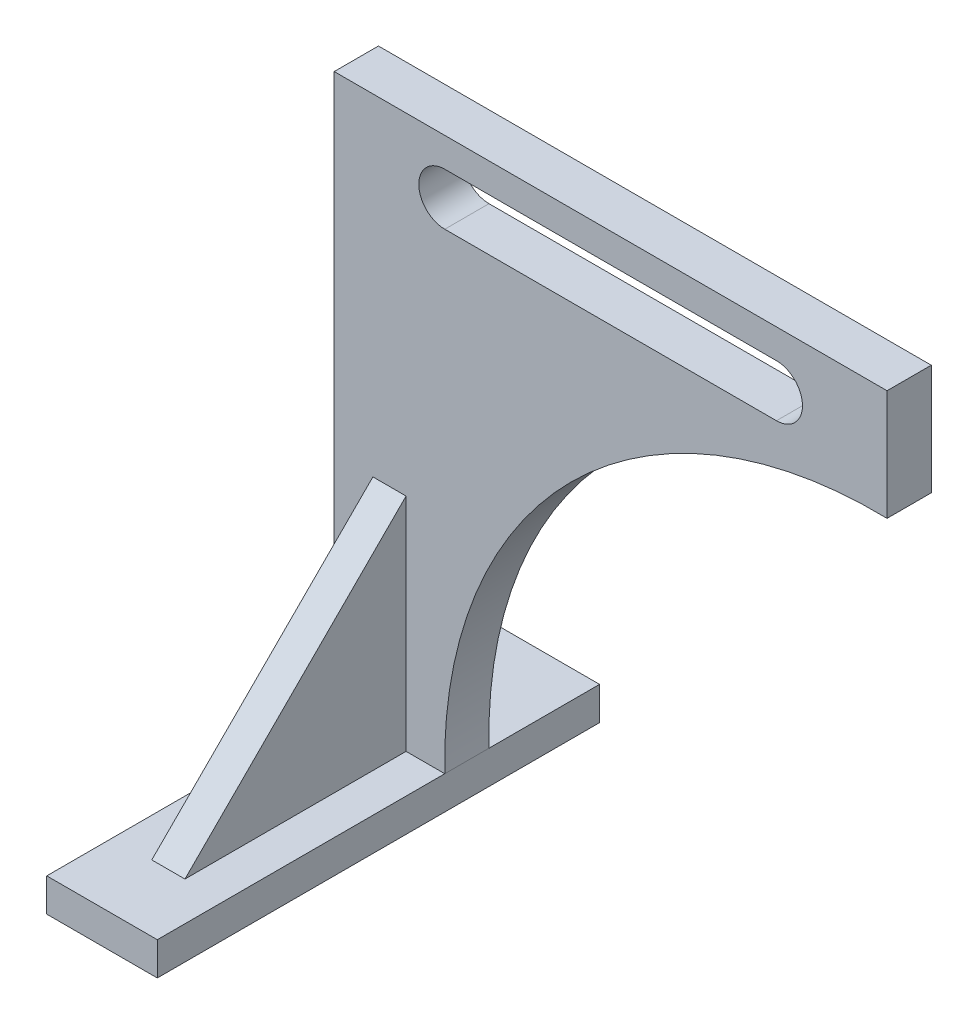
SolidWorks part; units mm, degrees
ref_plane "Front Plane" through (0, 0, 0) normal (0, 0, 1) x (1, 0, 0)
ref_plane "Top Plane" through (0, 0, 0) normal (0, 1, 0) x (1, 0, 0)
ref_plane "Right Plane" through (0, 0, 0) normal (1, 0, 0) x (0, 0, -1)
sketch "Sketch1" plane through (0, 0, 0) normal (0, 1, 0) x (1, 0, 0)
  line L1 (25, -100) -> (-25, -100)
  line L2 (25, -100) -> (25, 100)
  line L3 (25, 100) -> (-25, 100)
  line L4 (-25, -100) -> (-25, 100)
  line L5 (25, -100) -> (-25, 100) construction
  line L6 (25, 100) -> (-25, -100) construction
  point P0 (0, 0)
  dimension "D1" = 200
  dimension "D2" = 50
extrude "Boss-Extrude1" add sketch "Sketch1" along normal blind 15
ref_plane "Plane1" through (0, 0, -30) normal (0, 0, -1) x (-1, 0, 0)
sketch "Sketch2" plane through (0, 0, -30) normal (0, 0, -1) x (-1, 0, 0)
  line L0 (25, 15) -> (25, 265)
  line L1 (-25, 0) -> (25, 0) construction
  line L2 (25, 265) -> (-225, 265)
  line L3 (-225, 265) -> (-225, 215)
  line L4 (25, 15) -> (-25, 15)
  line L5 (-25, 240) -> (-175, 240) construction
  line L6 (-25, 228.25) -> (-175, 228.25)
  line L7 (-25, 251.75) -> (-175, 251.75)
  arc A0 (-25, 15) -> (-225, 215) centre (-220.242, 19.758) ccw
  arc A1 (-25, 228.25) -> (-25, 251.75) centre (-25, 240) ccw
  arc A2 (-175, 251.75) -> (-175, 228.25) centre (-175, 240) ccw
  point P12 (-100, 240)
  dimension "D4" = 390.6
  dimension "D5" = 11.75
  dimension "D1" = 265
  dimension "D2" = 250
  dimension "D3" = 50
  dimension "D6" = 25
  dimension "D7" = 50
  dimension "D8" = 150
extrude "Boss-Extrude2" add sketch "Sketch2" along normal blind 20
ref_plane "Plane2" through (-7.5, 0, 0) normal (-1, 0, 0) x (0, 0, 1)
sketch "Sketch4" plane through (-7.5, 0, 0) normal (-1, 0, 0) x (0, 0, 1)
  line L0 (-30, 115) -> (70, 15)
  line L2 (100, 15) -> (-30, 15) construction
  line L3 (70, 15) -> (-30, 15)
  line L4 (-30, 15) -> (-30, 115)
  point P2 (0, 0)
  dimension "D1" = 100
  dimension "D2" = 100
extrude "Boss-Extrude3" add sketch "Sketch4" against normal blind 15
